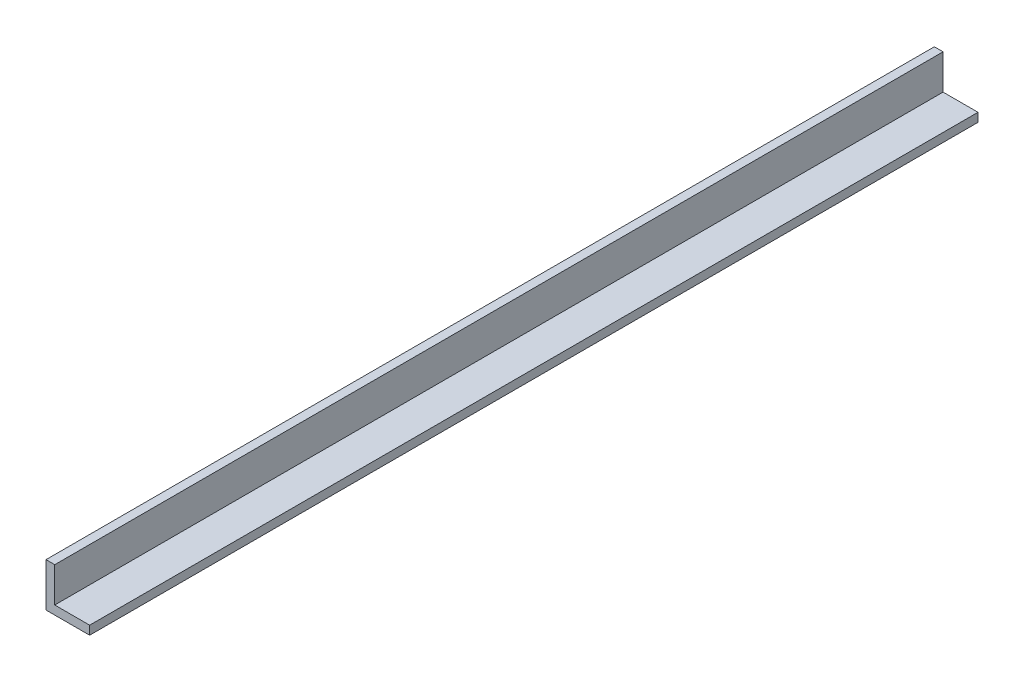
SolidWorks part; units mm, degrees
ref_plane "Front" through (0, 0, 0) normal (0, 0, 1) x (1, 0, 0)
ref_plane "Top" through (0, 0, 0) normal (0, 1, 0) x (1, 0, 0)
ref_plane "Right" through (0, 0, 0) normal (1, 0, 0) x (0, 0, -1)
sketch "Эскиз1" plane through (0, 0, 0) normal (0, 0, 1) x (1, 0, 0)
  line L0 (-10, 20) -> (-10, 0)
  line L1 (-10, 0) -> (10, 0)
  line L2 (10, 0) -> (10, 4)
  line L3 (10, 4) -> (-6, 4)
  line L4 (-6, 4) -> (-6, 20)
  line L5 (-6, 20) -> (-10, 20)
  dimension "D1" = 20
  dimension "D2" = 4
extrude "Бобышка-Вытянуть1" add sketch "Эскиз1" along normal blind 407
